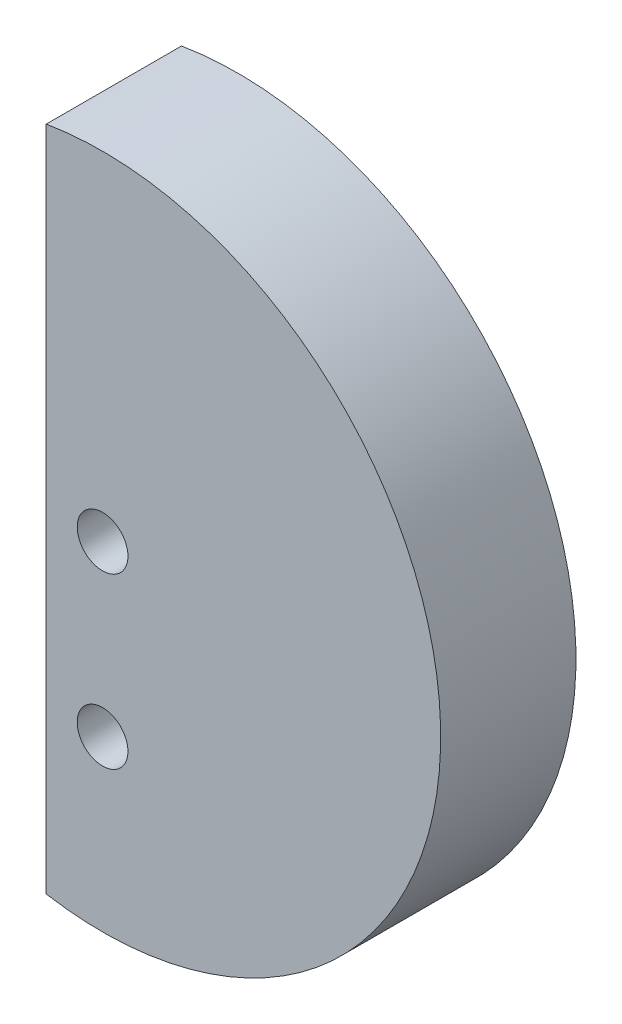
SolidWorks part; units mm, degrees
ref_plane "Front Plane" through (0, 0, 0) normal (0, 0, 1) x (1, 0, 0)
ref_plane "Top Plane" through (0, 0, 0) normal (0, 1, 0) x (1, 0, 0)
ref_plane "Right Plane" through (0, 0, 0) normal (1, 0, 0) x (0, 0, -1)
sketch "Sketch1" plane through (0, 0, 0) normal (0, 0, 1) x (1, 0, 0)
  line L0 (0, 0) -> (0, -15) construction
  circle A0 centre (0, 0) radius 30
  circle A1 centre (0, 0) radius 2.25
  circle A2 centre (0, -15) radius 2.25
  dimension "D1" = 60
  dimension "D2" = 4.5
  dimension "D4" = 4.5
  dimension "D3" = 15
extrude "Boss-Extrude1" add sketch "Sketch1" along normal blind 12
sketch "Sketch2" plane through (0, 0, 12) normal (0, 0, 1) x (1, 0, 0)
  line L1 (-5, 30) -> (-35, 30)
  line L2 (-5, 30) -> (-5, -30)
  line L3 (-5, -30) -> (-35, -30)
  line L4 (-35, 30) -> (-35, -30)
  dimension "D1" = 60
  dimension "D2" = 5
  dimension "D3" = 30
  dimension "D4" = 30
extrude "Cut-Extrude1" cut sketch "Sketch2" against normal up to surface (12 mm away) up to face at (30, 0, 0)
